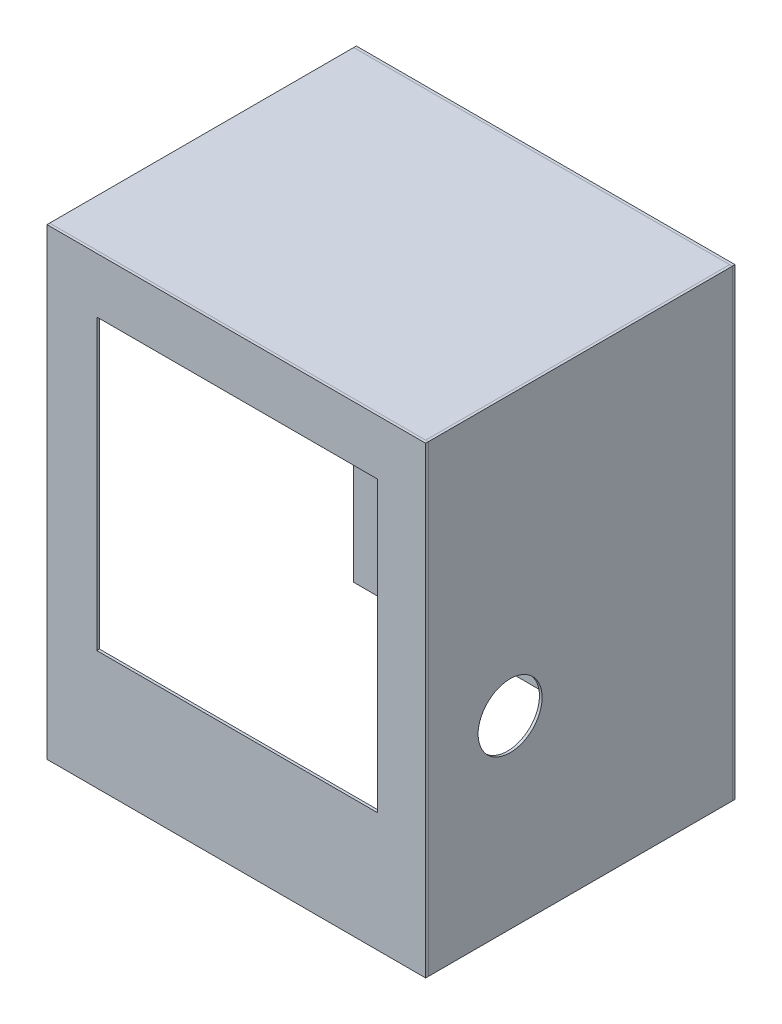
SolidWorks part; units mm, degrees
material "PP Copolymer"
ref_plane "Front Plane" through (0, 0, 0) normal (0, 0, 1) x (1, 0, 0)
ref_plane "Top Plane" through (0, 0, 0) normal (0, 1, 0) x (1, 0, 0)
ref_plane "Right Plane" through (0, 0, 0) normal (1, 0, 0) x (0, 0, -1)
sketch "Sketch1" plane through (0, 0, 0) normal (0, 0, 1) x (1, 0, 0)
  line L1 (0, 0) -> (676.275, 0)
  line L2 (0, 0) -> (0, 827.0875)
  line L3 (0, 827.0875) -> (676.275, 827.0875)
  line L4 (676.275, 0) -> (676.275, 827.0875)
  dimension "D1" = 827.0875
  dimension "D2" = 676.275
extrude "Boss-Extrude1" add sketch "Sketch1" along normal blind 4.7625
sketch "Sketch2" plane through (0, 0, 0) normal (0, 0, -1) x (-1, 0, 0)
  line L0 (0, 0) -> (-676.275, 0) construction
  line L1 (-676.275, 827.0875) -> (-671.5125, 827.0875)
  line L2 (-676.275, 827.0875) -> (-676.275, 0)
  line L3 (-676.275, 0) -> (-671.5125, 0)
  line L4 (-671.5125, 827.0875) -> (-671.5125, 0)
  dimension "D1" = 4.7625
extrude "Boss-Extrude2" add sketch "Sketch2" along normal blind 542.925 separate body
sketch "Sketch7" plane through (0, 0, -542.925) normal (0, 0, -1) x (-1, 0, 0)
  line L0 (-671.5125, 827.0875) -> (-676.275, 827.0875) construction
  line L1 (-676.275, 827.0875) -> (0, 827.0875)
  line L2 (-676.275, 827.0875) -> (-676.275, 0)
  line L3 (-676.275, 0) -> (0, 0)
  line L4 (0, 827.0875) -> (0, 0)
  line L5 (-676.275, 827.0875) -> (-676.275, 0) construction
  dimension "D1" = 676.275
extrude "Boss-Extrude4" add sketch "Sketch7" along normal blind 4.7625 separate body
sketch "Sketch8" plane through (0, 827.0875, 0) normal (0, 1, 0) x (1, 0, 0)
  line L1 (671.5125, 542.925) -> (0, 542.925)
  line L2 (671.5125, 542.925) -> (671.5125, 0)
  line L3 (671.5125, 0) -> (0, 0)
  line L4 (0, 542.925) -> (0, 0)
extrude "Boss-Extrude6" add sketch "Sketch8" against normal blind 4.7625 separate body
sketch "Sketch9" plane through (0, 0, 4.7625) normal (0, 0, 1) x (1, 0, 0)
  line L0 (676.275, 827.0875) -> (0, 827.0875) construction
  line L1 (88.9, 728.6625) -> (590.55, 728.6625)
  line L2 (88.9, 728.6625) -> (88.9, 212.725)
  line L3 (88.9, 212.725) -> (590.55, 212.725)
  line L4 (590.55, 728.6625) -> (590.55, 212.725)
  line L5 (88.9, 728.6625) -> (590.55, 212.725) construction
  line L6 (88.9, 212.725) -> (590.55, 728.6625) construction
  line L9 (0, 0) -> (676.275, 0) construction
  line L10 (676.275, 0) -> (676.275, 827.0875) construction
  line L11 (0, 827.0875) -> (0, 0) construction
  point P0 (339.725, 470.6938)
  dimension "D1" = 98.425
  dimension "D2" = 212.725
  dimension "D3" = 85.725
  dimension "D4" = 88.9
extrude "Cut-Extrude1" cut sketch "Sketch9" against normal up to next (4.7625 mm away)
sketch "Sketch10" plane through (676.275, 0, 0) normal (1, 0, 0) x (0, 0, -1)
  line L0 (542.925, 0) -> (0, 0) construction
  line L1 (0, 0) -> (0, 827.0875) construction
  circle A0 centre (146.05, 330.2) radius 57.15
  dimension "D1" = 114.3
  dimension "D2" = 330.2
  dimension "D3" = 146.05
extrude "Cut-Extrude2" cut sketch "Sketch10" against normal through all
